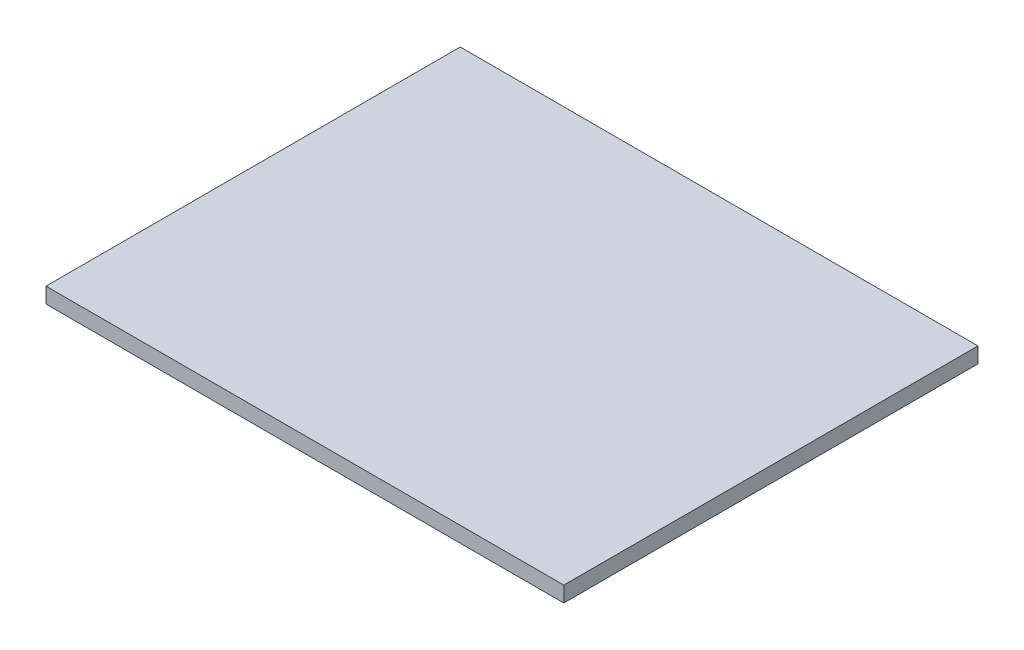
SolidWorks part; units mm, degrees
ref_plane "정면" through (0, 0, 0) normal (0, 0, 1) x (1, 0, 0)
ref_plane "윗면" through (0, 0, 0) normal (0, 1, 0) x (1, 0, 0)
ref_plane "우측면" through (0, 0, 0) normal (1, 0, 0) x (0, 0, -1)
sketch "스케치1" plane through (0, 0, 0) normal (0, 1, 0) x (1, 0, 0)
  line L1 (0, 0) -> (100, 0)
  line L2 (0, 0) -> (0, 80)
  line L3 (0, 80) -> (100, 80)
  line L4 (100, 0) -> (100, 80)
  dimension "D1" = 100
  dimension "D2" = 80
extrude "보스-돌출1" add sketch "스케치1" along normal blind 3
sketch "스케치2" plane through (0, 3, 0) normal (0, 1, 0) x (1, 0, 0)
  line L0 (50, 80) -> (50, 40) construction
  line L1 (100, 80) -> (0, 80) construction
  line L2 (50, 40) -> (50, 0) construction
  line L3 (0, 0) -> (100, 0) construction
